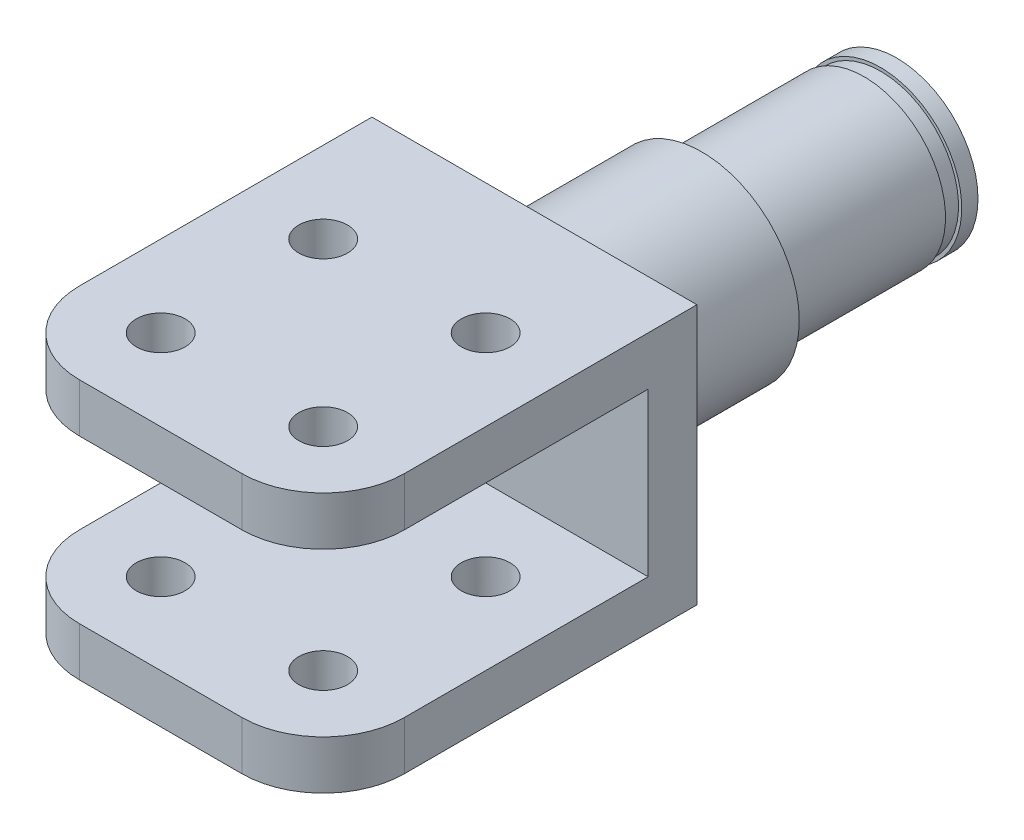
SolidWorks part; units mm, degrees
material "1060 合金"
ref_plane "前视基准面" through (0, 0, 0) normal (0, 0, 1) x (1, 0, 0)
ref_plane "上视基准面" through (0, 0, 0) normal (0, 1, 0) x (1, 0, 0)
ref_plane "右视基准面" through (0, 0, 0) normal (1, 0, 0) x (0, 0, -1)
sketch "草图1" plane through (0, 0, 0) normal (0, 0, 1) x (1, 0, 0)
  circle A0 centre (0, 0) radius 5
  dimension "D1" = 10
extrude "凸台-拉伸1" add sketch "草图1" along normal blind 12
ref_plane "基准面1" through (0, 0, 1) normal (0, 0, -1) x (-1, 0, 0)
sketch "草图2" plane through (0, 0, 1) normal (0, 0, -1) x (-1, 0, 0)
  circle A0 centre (0, 0) radius 5
  circle A1 centre (0, 0) radius 4.8
  dimension "D1" = 10
  dimension "D2" = 9.6
extrude "切除-拉伸1" cut sketch "草图2" against normal blind 1
sketch "草图3" plane through (0, 0, 12) normal (0, 0, 1) x (1, 0, 0)
  circle A0 centre (0, 0) radius 6
  dimension "D1" = 12
extrude "凸台-拉伸2" add sketch "草图3" along normal blind 10.3
sketch "草图4" plane through (0, 0, 22.3) normal (0, 0, 1) x (1, 0, 0)
  line L1 (-10, 8) -> (10, 8)
  line L2 (-10, 8) -> (-10, -8)
  line L3 (-10, -8) -> (10, -8)
  line L4 (10, 8) -> (10, -8)
  line L5 (-10, 8) -> (10, -8) construction
  line L6 (-10, -8) -> (10, 8) construction
  point P0 (0, 0)
  dimension "D1" = 16
  dimension "D2" = 20
extrude "凸台-拉伸3" add sketch "草图4" along normal blind 23
sketch "草图5" plane through (0, 0, 45.3) normal (0, 0, 1) x (1, 0, 0)
  line L1 (-10, 5) -> (10, 5)
  line L2 (-10, 5) -> (-10, -5)
  line L3 (-10, -5) -> (10, -5)
  line L4 (10, 5) -> (10, -5)
  line L5 (-10, 5) -> (10, -5) construction
  line L6 (-10, -5) -> (10, 5) construction
  point P0 (0, 0)
  dimension "D1" = 10
  dimension "D2" = 20
extrude "切除-拉伸3" cut sketch "草图5" against normal blind 20
sketch "草图6" plane through (0, 8, 0) normal (0, 1, 0) x (1, 0, 0)
  line L5 (10, -45.3) -> (10, -22.3) construction
  line L6 (5, -30.3) -> (-5, -30.3) construction
  line L8 (5, -30.3) -> (5, -40.3) construction
  line L9 (5, -40.3) -> (-5, -40.3) construction
  line L10 (-5, -30.3) -> (-5, -40.3) construction
  line L11 (5, -30.3) -> (-5, -40.3) construction
  line L12 (5, -40.3) -> (-5, -30.3) construction
  line L13 (10, -45.3) -> (-10, -45.3) construction
  circle A2 centre (5, -40.3) radius 1.5
  circle A3 centre (-5, -40.3) radius 1.5
  circle A4 centre (-5, -30.3) radius 1.5
  circle A5 centre (5, -30.3) radius 1.5
  point P0 (0, -35.3)
  dimension "D1" = 10
  dimension "D2" = 5
  dimension "D4" = 3
  dimension "D5" = 3
  dimension "D6" = 3
  dimension "D7" = 3
  dimension "D3" = 5
extrude "切除-拉伸4" cut sketch "草图6" against normal blind 20
fillet "圆角1" radius 5 4 edges at (-10, 6.5, 45.3) (-10, -6.5, 45.3) (10, -6.5, 45.3) (10, 6.5, 45.3)
sketch "草图7" plane through (0, 0, 0) normal (0, 0, -1) x (-1, 0, 0)
  circle A0 centre (0, 0) radius 2
  dimension "D1" = 4
extrude "切除-拉伸5" cut sketch "草图7" against normal through all
